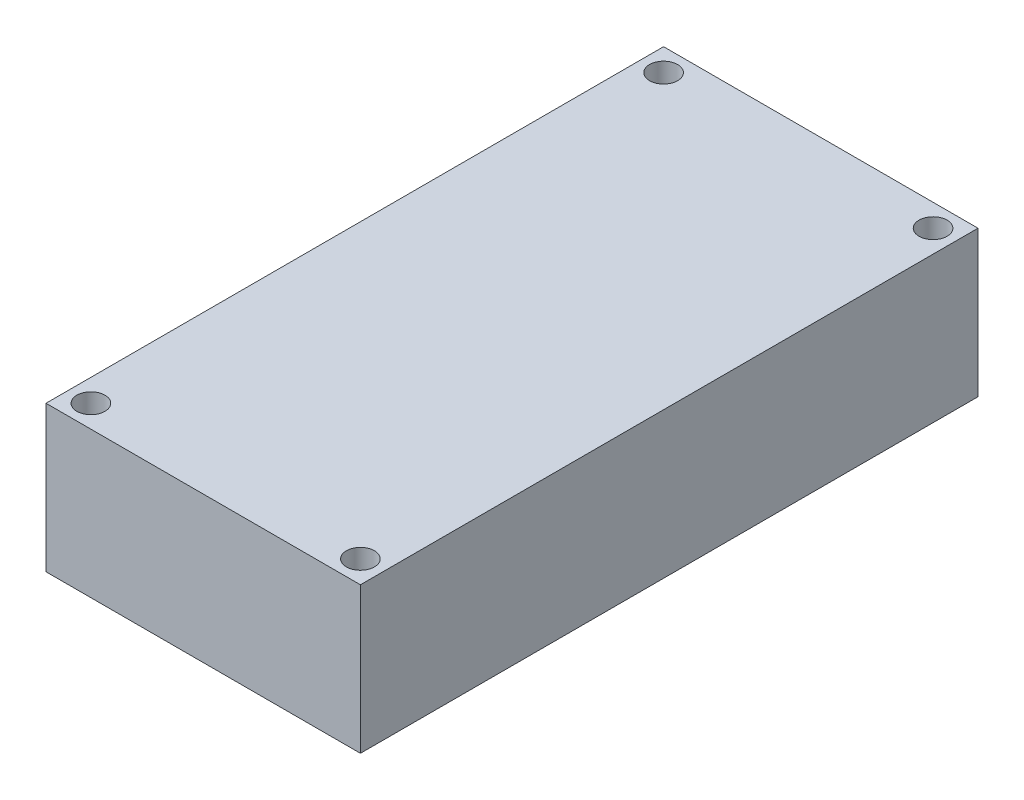
SolidWorks part; units mm, degrees
ref_plane "前视基准面" through (0, 0, 0) normal (0, 0, 1) x (1, 0, 0)
ref_plane "上视基准面" through (0, 0, 0) normal (0, 1, 0) x (1, 0, 0)
ref_plane "右视基准面" through (0, 0, 0) normal (1, 0, 0) x (0, 0, -1)
sketch "草图1" plane through (0, 0, 0) normal (0, 0, 1) x (1, 0, 0)
  line L0 (0, 30.199) -> (0, -24.5864) construction
  line L1 (-32.0838, 0) -> (36.6073, 0) construction
  line L2 (14, 6.5) -> (-14, 6.5)
  line L3 (-14, 6.5) -> (-14, -6.5)
  line L4 (14, 6.5) -> (14, -6.5)
  line L5 (14, -6.5) -> (-14, -6.5)
  point P5 (0, -6.5)
  point P10 (0, 6.5)
  point P12 (14, 0)
  point P13 (-14, 0)
  dimension "D1" = 13
  dimension "D2" = 28
extrude "凸台-拉伸1" add sketch "草图1" along normal mid plane 55
sketch "Sketch1" plane through (0, 6.5, 0) normal (0, 1, 0) x (1, 0, 0)
  line L0 (0, 43.0013) -> (0, -44.4916) construction
  line L1 (-30.3316, 0) -> (22.8625, 0) construction
  line L2 (14, 27.5) -> (-14, 27.5) construction
  line L3 (14, -27.5) -> (14, 27.5) construction
  circle A0 centre (-12, 25.5) radius 1.25
  circle A1 centre (12, 25.5) radius 1.25
  circle A2 centre (12, -25.5) radius 1.25
  circle A3 centre (-12, -25.5) radius 1.25
  dimension "D1" = 2.5
  dimension "D2" = 2
  dimension "D3" = 2
extrude "Cut-Extrude1" cut sketch "Sketch1" against normal through all
